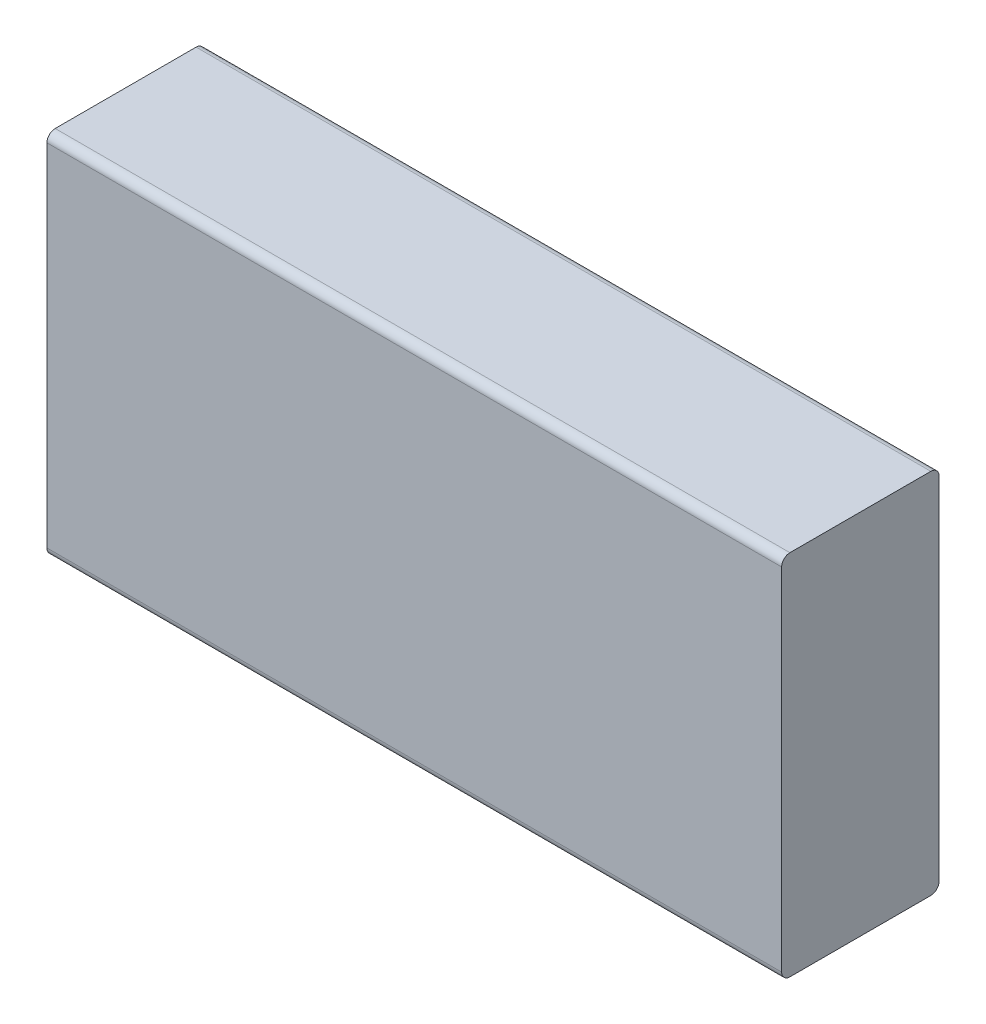
SolidWorks part; units mm, degrees
ref_plane "Front Plane" through (0, 0, 0) normal (0, 0, 1) x (1, 0, 0)
ref_plane "Top Plane" through (0, 0, 0) normal (0, 1, 0) x (1, 0, 0)
ref_plane "Right Plane" through (0, 0, 0) normal (1, 0, 0) x (0, 0, -1)
sketch "Sketch1" plane through (0, 0, 0) normal (1, 0, 0) x (0, -1, 0)
  line L1 (-44.45, -19.05) -> (44.45, -19.05)
  line L2 (-44.45, -19.05) -> (-44.45, 19.05)
  line L3 (-44.45, 19.05) -> (44.45, 19.05)
  line L4 (44.45, -19.05) -> (44.45, 19.05)
  line L5 (-44.45, -19.05) -> (44.45, 19.05) construction
  line L6 (-44.45, 19.05) -> (44.45, -19.05) construction
  point P0 (0, 0)
  dimension "D1" = 38.1
  dimension "D2" = 88.9
extrude "Boss-Extrude1" add sketch "Sketch1" along normal blind 177.8
fillet "Fillet1" radius 2 4 edges at (88.9, 44.45, -19.05) (88.9, -44.45, -19.05) (88.9, -44.45, 19.05) (88.9, 44.45, 19.05)
